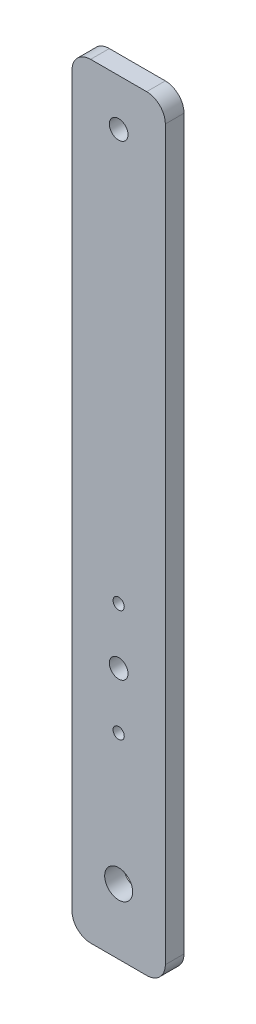
SolidWorks part; units mm, degrees
ref_plane "Front Plane" through (0, 0, 0) normal (0, 0, 1) x (1, 0, 0)
ref_plane "Top Plane" through (0, 0, 0) normal (0, 1, 0) x (1, 0, 0)
ref_plane "Right Plane" through (0, 0, 0) normal (1, 0, 0) x (0, 0, -1)
sketch "Sketch1" plane through (0, 0, 0) normal (0, 0, 1) x (1, 0, 0)
  line L1 (0, 0) -> (50, 0)
  line L2 (0, 0) -> (0, -410)
  line L3 (0, -410) -> (50, -410)
  line L4 (50, 0) -> (50, -410)
  circle A0 centre (25, -275) radius 5
  circle A1 centre (25, -25) radius 5
  circle A2 centre (25, -245) radius 3
  circle A3 centre (25, -305) radius 3
  dimension "D3" = 10
  dimension "D6" = 250
  dimension "D4" = 30
  dimension "D1" = 50
  dimension "D2" = 410
  dimension "D5" = 25
  dimension "D7" = 25
  dimension "D8" = 30
extrude "Boss-Extrude1" add sketch "Sketch1" along normal blind 10
fillet "Fillet1" radius 10 4 edges at (0, 0, 5) (50, 0, 5) (0, -410, 5) (50, -410, 5)
sketch "Sketch2" plane through (0, 0, 10) normal (0, 0, 1) x (1, 0, 0)
  line L0 (50, -400) -> (50, -10) construction
  line L2 (10, -410) -> (40, -410) construction
  circle A0 centre (25, -375) radius 7.5
  dimension "D1" = 25
  dimension "D2" = 35
extrude "Cut-Extrude1" cut sketch "Sketch2" against normal blind 10
